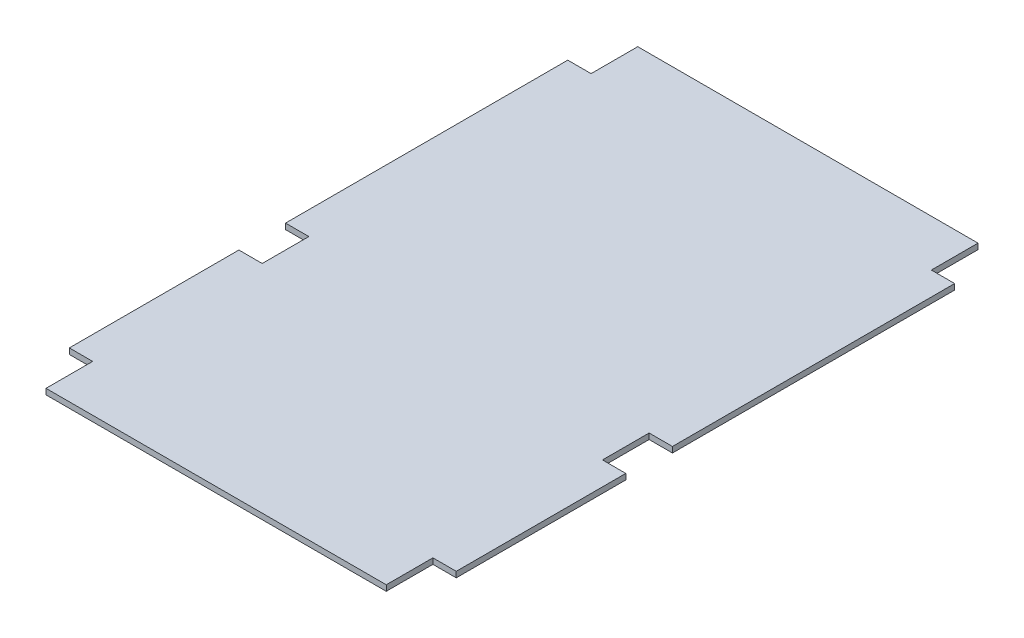
SolidWorks part; units mm, degrees
material "ABS PC"
ref_plane "정면" through (0, 0, 0) normal (0, 0, 1) x (1, 0, 0)
ref_plane "윗면" through (0, 0, 0) normal (0, 1, 0) x (1, 0, 0)
ref_plane "우측면" through (0, 0, 0) normal (1, 0, 0) x (0, 0, -1)
sketch "스케치1" plane through (0, 0, 0) normal (0, 1, 0) x (1, 0, 0)
  line L1 (0, 0) -> (340, 0)
  line L2 (0, 0) -> (0, 520)
  line L3 (0, 520) -> (340, 520)
  line L4 (340, 0) -> (340, 520)
  dimension "D1" = 340
  dimension "D2" = 520
extrude "보스-돌출1" add sketch "스케치1" along normal blind 5
sketch "스케치2" plane through (0, 5, 0) normal (0, 1, 0) x (1, 0, 0)
  line L0 (319.5, 479) -> (319.5, 41) construction
  line L1 (340, 520) -> (319.5, 520)
  line L2 (340, 520) -> (340, 479)
  line L3 (340, 479) -> (319.5, 479)
  line L4 (319.5, 520) -> (319.5, 479)
  line L5 (340, 0) -> (319.5, 0)
  line L6 (340, 0) -> (340, 41)
  line L7 (340, 41) -> (319.5, 41)
  line L8 (319.5, 0) -> (319.5, 41)
  line L9 (0, 0) -> (20.5, 0)
  line L10 (0, 0) -> (0, 41)
  line L11 (0, 41) -> (20.5, 41)
  line L12 (20.5, 0) -> (20.5, 41)
  line L13 (0, 520) -> (20.5, 520)
  line L14 (0, 520) -> (0, 479)
  line L15 (0, 479) -> (20.5, 479)
  line L16 (20.5, 520) -> (20.5, 479)
  line L17 (20.5, 41) -> (319.5, 41) construction
  line L18 (20.5, 479) -> (20.5, 41) construction
  line L19 (20.5, 479) -> (319.5, 479) construction
  dimension "D1" = 20.5
  dimension "D2" = 41
  dimension "D3" = 41
  dimension "D4" = 20.5
extrude "컷-돌출1" cut sketch "스케치2" against normal through all
sketch "스케치3" plane through (0, 5, 0) normal (0, 1, 0) x (1, 0, 0)
  line L0 (340, 41) -> (340, 479) construction
  line L1 (340, 231) -> (319.5, 231)
  line L2 (340, 231) -> (340, 190)
  line L3 (340, 190) -> (319.5, 190)
  line L4 (319.5, 231) -> (319.5, 190)
  line L5 (0, 479) -> (0, 41) construction
  line L6 (0, 231) -> (20.5, 231)
  line L7 (0, 231) -> (0, 190)
  line L8 (0, 190) -> (20.5, 190)
  line L9 (20.5, 231) -> (20.5, 190)
  line L10 (319.5, 231) -> (20.5, 231) construction
  line L11 (319.5, 190) -> (20.5, 190) construction
  line L12 (20.5, 0) -> (319.5, 0) construction
  dimension "D1" = 20.5
  dimension "D2" = 41
  dimension "D3" = 190
extrude "컷-돌출2" cut sketch "스케치3" against normal blind 15
